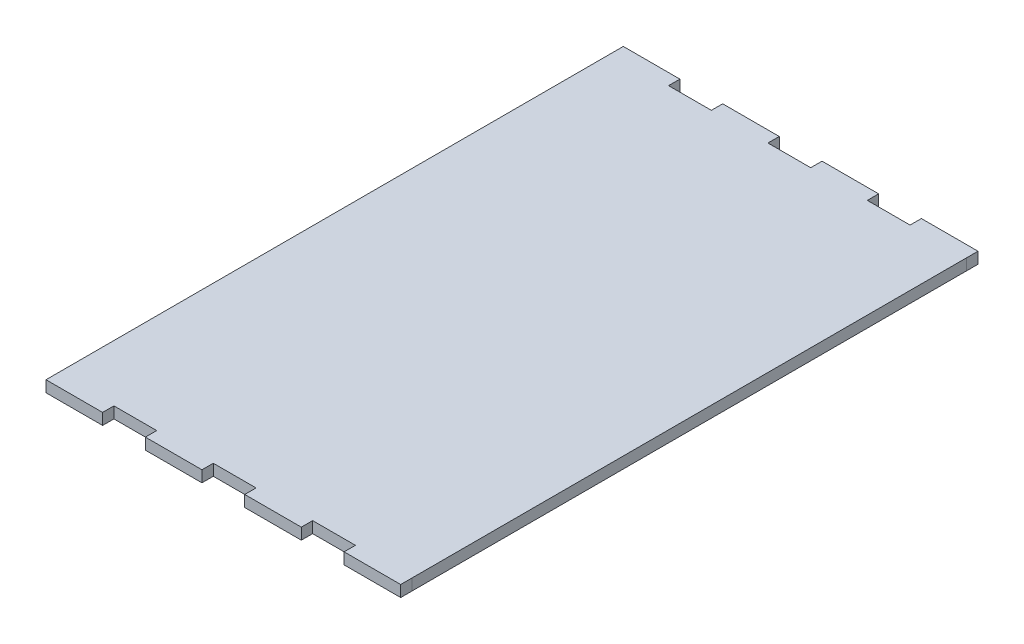
SolidWorks part; units mm, degrees
ref_plane "Plan de face" through (0, 0, 0) normal (0, 0, 1) x (1, 0, 0)
ref_plane "Plan de dessus" through (0, 0, 0) normal (0, 1, 0) x (1, 0, 0)
ref_plane "Plan de droite" through (0, 0, 0) normal (1, 0, 0) x (0, 0, -1)
sketch "Esquisse1" plane through (0, 0, 0) normal (0, 1, 0) x (1, 0, 0)
  line L1 (30, 0) -> (52.67, 0)
  line L2 (0, 0) -> (0, 294)
  line L4 (188, 0) -> (188, 294)
  line L6 (0, 0) -> (0, -6)
  line L7 (0, -6) -> (30, -6)
  line L8 (30, 0) -> (30, -6)
  line L9 (52.67, 0) -> (52.67, -6)
  line L10 (52.67, -6) -> (82.67, -6)
  line L11 (82.67, 0) -> (82.67, -6)
  line L13 (105.34, 0) -> (105.34, -6)
  line L14 (105.34, -6) -> (135.34, -6)
  line L15 (135.34, 0) -> (135.34, -6)
  line L16 (188, 0) -> (188.01, 0)
  line L17 (158.01, 0) -> (158.01, -6)
  line L18 (158.01, -6) -> (188.01, -6)
  line L19 (188.01, 0) -> (188.01, -6)
  line L20 (82.67, 0) -> (105.34, 0)
  line L21 (135.34, 0) -> (158.01, 0)
  line L22 (188, 147) -> (0, 147) construction
  line L25 (188.01, 294) -> (188.01, 300)
  line L26 (158.01, 300) -> (188.01, 300)
  line L27 (158.01, 294) -> (158.01, 300)
  line L28 (188, 294) -> (188.01, 294)
  line L29 (135.34, 294) -> (135.34, 300)
  line L30 (105.34, 300) -> (135.34, 300)
  line L31 (105.34, 294) -> (105.34, 300)
  line L32 (82.67, 294) -> (82.67, 300)
  line L33 (52.67, 300) -> (82.67, 300)
  line L34 (52.67, 294) -> (52.67, 300)
  line L35 (30, 294) -> (30, 300)
  line L36 (0, 300) -> (30, 300)
  line L37 (0, 294) -> (0, 300)
  line L38 (30, 294) -> (52.67, 294)
  line L39 (82.67, 294) -> (105.34, 294)
  line L40 (135.34, 294) -> (158.01, 294)
  dimension "D1" = 188
  dimension "D2" = 294
  dimension "D3" = 30
  dimension "D4" = 6
  dimension "D5" = 4
extrude "Boss.-Extru.2" add sketch "Esquisse1" along normal blind 6
